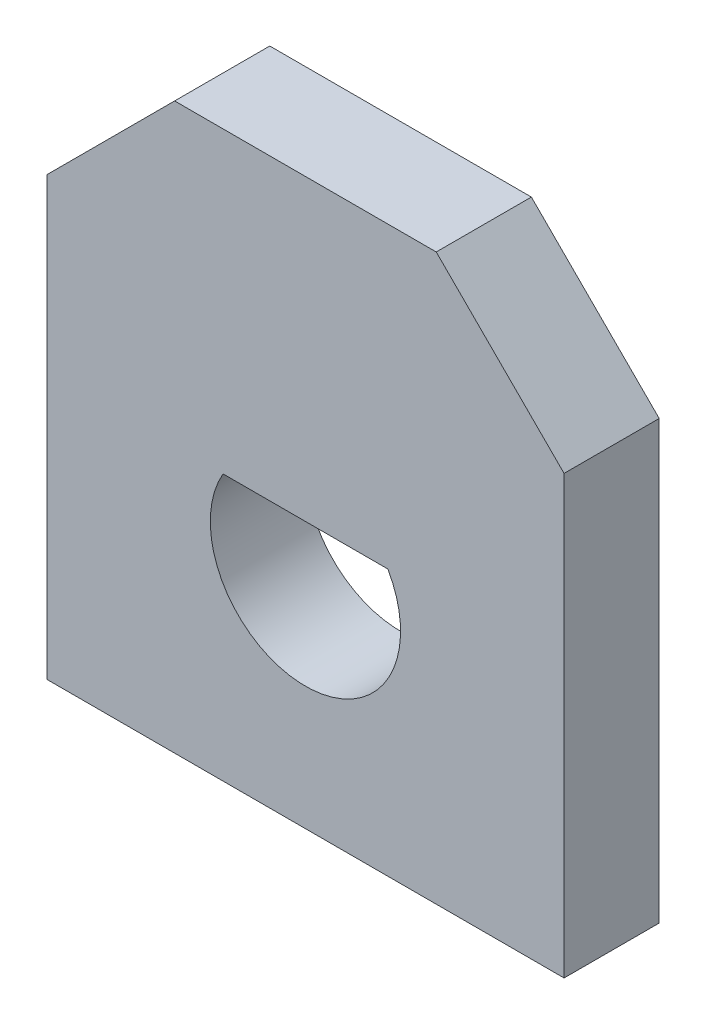
SolidWorks part; units mm, degrees
ref_plane "Front" through (0, 0, 0) normal (0, 0, 1) x (1, 0, 0)
ref_plane "Top" through (0, 0, 0) normal (0, 1, 0) x (1, 0, 0)
ref_plane "Right" through (0, 0, 0) normal (1, 0, 0) x (0, 0, -1)
sketch "Sketch1" plane through (0, 0, 0) normal (0, 0, 1) x (1, 0, 0)
  line L0 (-2.794, 7.3978) -> (2.794, 7.3978)
  line L1 (-5.5245, 4.6672) -> (5.5245, 4.6672)
  line L2 (-5.5245, 4.6672) -> (-5.5245, -4.6672)
  line L3 (-5.5245, -4.6672) -> (5.5245, -4.6672)
  line L4 (5.5245, 4.6672) -> (5.5245, -4.6672)
  line L5 (-5.5245, 4.6672) -> (5.5245, -4.6672) construction
  line L6 (-5.5245, -4.6672) -> (5.5245, 4.6672) construction
  line L7 (0, 0) -> (0, 7.3978) construction
  line L8 (-5.5245, 4.6672) -> (-2.794, 7.3978)
  line L9 (2.794, 7.3978) -> (5.5245, 4.6672)
  line L10 (-1.7598, 1.016) -> (1.7598, 1.016)
  line L11 (0, -2.032) -> (0, 1.016) construction
  circle A0 centre (0, 0) radius 2.032
  point P0 (0, 0)
  dimension "D5" = 4.064
  dimension "D1" = 11.049
  dimension "D2" = 45
  dimension "D3" = 5.588
  dimension "D4" = 12.065
  dimension "D6" = 3.048
extrude "Boss-Extrude1" add sketch "Sketch1" along normal blind 2.032 contours L4 L1 L2 L3 A0 | L9 L0 L8 L1 | L10 A0
